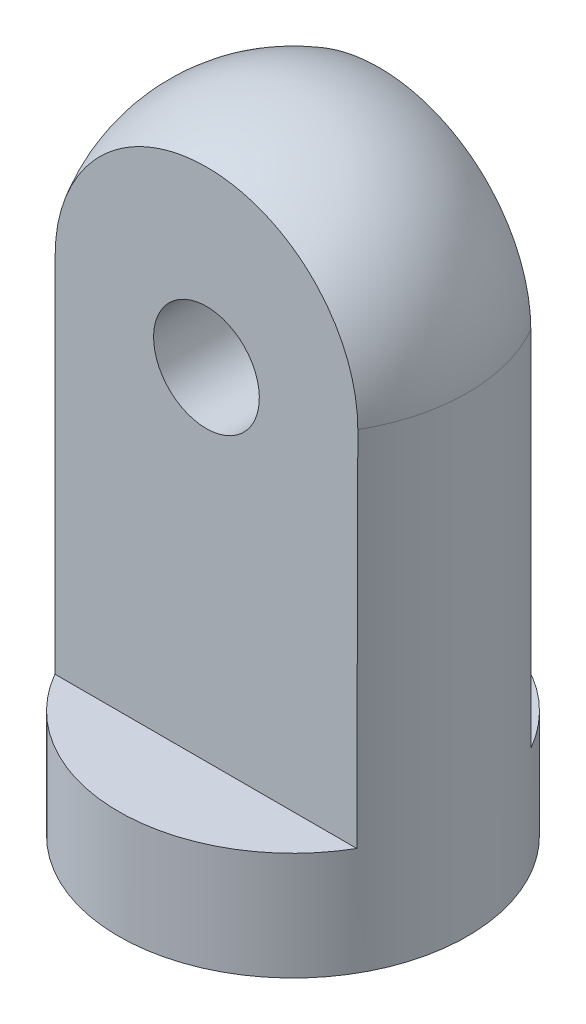
SolidWorks part; units mm, degrees
ref_plane "Front Plane" through (0, 0, 0) normal (0, 0, 1) x (1, 0, 0)
ref_plane "Top Plane" through (0, 0, 0) normal (0, 1, 0) x (1, 0, 0)
ref_plane "Right Plane" through (0, 0, 0) normal (1, 0, 0) x (0, 0, -1)
sketch "Sketch3" plane through (0, 0, 0) normal (0, 0, 1) x (1, 0, 0)
  line L0 (0, 46.99) -> (0, 0)
  line L1 (0, 0) -> (12.7, 0)
  line L2 (12.7, 0) -> (12.7, 34.29)
  arc A0 (0, 46.99) -> (12.7, 34.29) centre (0, 34.29) cw
  point P6 (0.7607, 10.0437)
  point P7 (0, 0)
  dimension "D1" = 12.7
  dimension "D2" = 46.99
revolve "Revolve1" add sketch "Sketch3" angle 360 about L0
sketch "Sketch4" plane through (0, 0, 0) normal (1, 0, 0) x (0, 0, -1)
  line L0 (9.058, 43.1918) -> (9.058, 7.8726)
  line L1 (9.058, 7.8726) -> (12.7, 7.8726)
  line L2 (12.7, 0) -> (12.7, 34.29) construction
  line L3 (-6.2833, 45.3268) -> (-6.35, 7.8726)
  line L4 (-6.35, 7.8726) -> (-12.7, 7.8726)
  line L5 (-12.7, 34.29) -> (-12.7, 0) construction
  line L6 (9.058, 43.1918) -> (24.713, 43.1918)
  line L7 (24.713, 43.1918) -> (24.713, 7.8726)
  line L8 (24.713, 7.8726) -> (12.7, 7.8726)
  line L9 (-6.2833, 45.3268) -> (-21.8848, 45.3268)
  line L10 (-21.8848, 45.3268) -> (-21.8848, 7.1992)
  line L11 (-21.8848, 7.1992) -> (-17.5079, 7.1992)
  line L12 (-17.5079, 7.1992) -> (-15.4714, 7.8726)
  line L13 (-15.4714, 7.8726) -> (-12.7, 7.8726)
  arc A0 (12.7, 34.29) -> (-12.7, 34.29) centre (0, 34.29) ccw construction
  point P10 (24.713, 43.1918)
  point P20 (-7.5463, 44.5049)
  point P21 (0, 0)
  point P22 (-6.35, 45.3268)
  dimension "D1" = 6.35
extrude "Cut-Extrude1" cut sketch "Sketch4" against normal through all both and the other way through all contours L3 L4 L13 L12 L11 L10 L9
mirror "Mirror1" about plane through (0, 0, 0) normal (0, 0, 1) of "Cut-Extrude1"
sketch "Sketch6" plane through (0, 0.0113, 6.364) normal (0, 0.0018, 1) x (1, 0, 0)
  circle A0 centre (0, 32.688) radius 3.8521
  dimension "D1" = 7.7041
extrude "Cut-Extrude2" cut sketch "Sketch6" against normal through all and the other way through all
